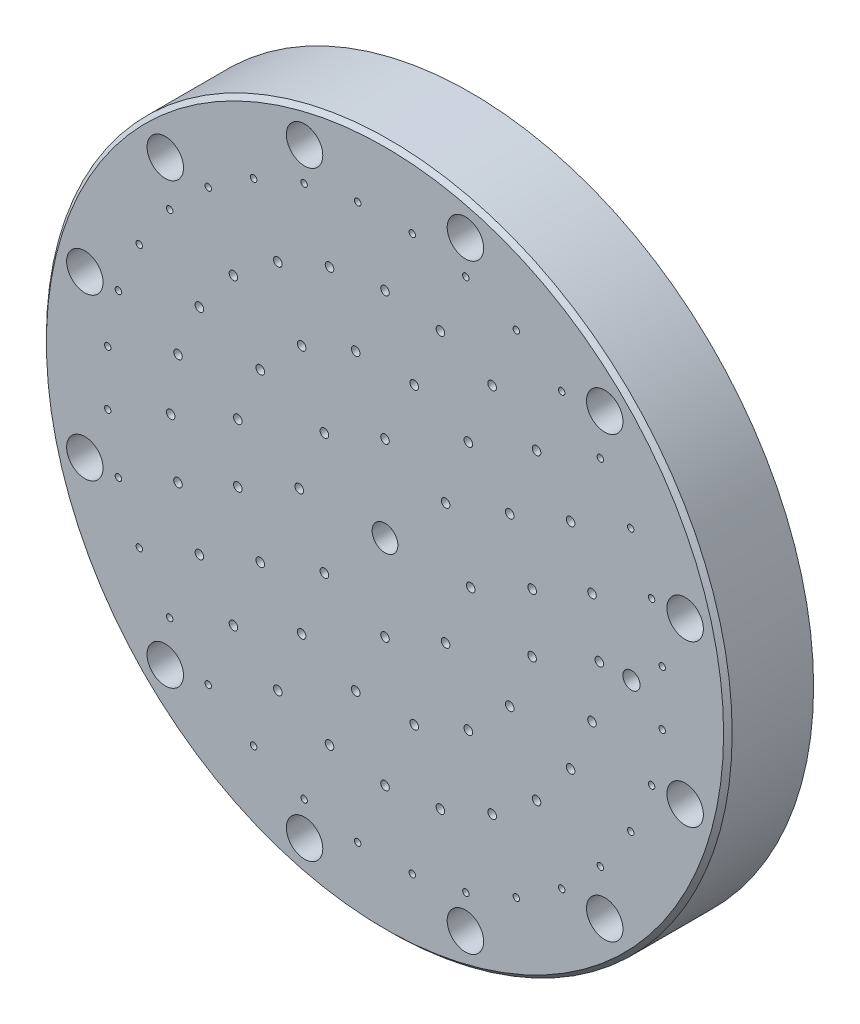
SolidWorks part; units mm, degrees
ref_plane "前视基准面" through (0, 0, 0) normal (0, 0, 1) x (1, 0, 0)
ref_plane "上视基准面" through (0, 0, 0) normal (0, 1, 0) x (1, 0, 0)
ref_plane "右视基准面" through (0, 0, 0) normal (1, 0, 0) x (0, 0, -1)
sketch "草图1" plane through (0, 0, 0) normal (0, 0, 1) x (1, 0, 0)
  circle A0 centre (0, 0) radius 80
extrude "凸台-拉伸1" add sketch "草图1" along normal blind 20
sketch "草图2" plane through (0, 0, 0) normal (0, 0, 1) x (1, 0, 0)
  circle A0 centre (0, 0) radius 23
  circle A1 centre (0, 0) radius 17
extrude "切除-拉伸1" cut sketch "草图2" along normal blind 8
sketch "草图3" plane through (0, 0, 0) normal (0, 0, 1) x (1, 0, 0)
  circle A0 centre (0, 0) radius 38
  circle A1 centre (0, 0) radius 32
extrude "切除-拉伸2" cut sketch "草图3" along normal blind 8
sketch "草图4" plane through (0, 0, 0) normal (0, 0, 1) x (1, 0, 0)
  circle A0 centre (0, 0) radius 53
  circle A1 centre (0, 0) radius 47
extrude "切除-拉伸3" cut sketch "草图4" along normal blind 8
sketch "草图5" plane through (0, 0, 0) normal (0, 0, 1) x (1, 0, 0)
  circle A0 centre (0, 0) radius 68
  circle A1 centre (0, 0) radius 62
extrude "切除-拉伸4" cut sketch "草图5" along normal blind 8
ref_plane "基准面1" through (0, 0, 8) normal (0, 0, 1) x (1, 0, 0)
sketch "草图6" plane through (0, 0, 8) normal (0, 0, 1) x (1, 0, 0)
  circle A0 centre (20, 0) radius 1
  circle A1 centre (14.1421, 14.1421) radius 1
  circle A2 centre (0, 20) radius 1
  circle A3 centre (-14.1421, 14.1421) radius 1
  circle A4 centre (-20, 0) radius 1
  circle A5 centre (-14.1421, -14.1421) radius 1
  circle A6 centre (0, -20) radius 1
  circle A7 centre (14.1421, -14.1421) radius 1
extrude "切除-拉伸5" cut sketch "草图6" along normal blind 12
sketch "草图7" plane through (0, 0, 8) normal (0, 0, 1) x (1, 0, 0)
  circle A0 centre (34.3275, 6.8282) radius 1
  circle A1 centre (29.1014, 19.445) radius 1
  circle A2 centre (19.445, 29.1014) radius 1
  circle A3 centre (6.8282, 34.3275) radius 1
  circle A4 centre (-6.8282, 34.3275) radius 1
  circle A5 centre (-19.445, 29.1014) radius 1
  circle A6 centre (-29.1014, 19.445) radius 1
  circle A7 centre (-34.3275, 6.8282) radius 1
  circle A8 centre (-34.3275, -6.8282) radius 1
  circle A9 centre (-29.1014, -19.445) radius 1
  circle A10 centre (-19.445, -29.1014) radius 1
  circle A11 centre (-6.8282, -34.3275) radius 1
  circle A12 centre (6.8282, -34.3275) radius 1
  circle A13 centre (19.445, -29.1014) radius 1
  circle A14 centre (29.1014, -19.445) radius 1
  circle A15 centre (34.3275, -6.8282) radius 1
extrude "切除-拉伸6" cut sketch "草图7" along normal blind 12
sketch "草图8" plane through (0, 0, 8) normal (0, 0, 1) x (1, 0, 0)
  circle A0 centre (50, 0) radius 1
  circle A1 centre (48.2963, 12.941) radius 1
  circle A2 centre (43.3013, 25) radius 1
  circle A3 centre (35.3553, 35.3553) radius 1
  circle A4 centre (25, 43.3013) radius 1
  circle A5 centre (12.941, 48.2963) radius 1
  circle A6 centre (0, 50) radius 1
  circle A7 centre (-12.941, 48.2963) radius 1
  circle A8 centre (-25, 43.3013) radius 1
  circle A9 centre (-35.3553, 35.3553) radius 1
  circle A10 centre (-43.3013, 25) radius 1
  circle A11 centre (-48.2963, 12.941) radius 1
  circle A12 centre (-50, 0) radius 1
  circle A13 centre (-48.2963, -12.941) radius 1
  circle A14 centre (-43.3013, -25) radius 1
  circle A15 centre (-35.3553, -35.3553) radius 1
  circle A16 centre (-25, -43.3013) radius 1
  circle A17 centre (-12.941, -48.2963) radius 1
  circle A18 centre (0, -50) radius 1
  circle A19 centre (12.941, -48.2963) radius 1
  circle A20 centre (25, -43.3013) radius 1
  circle A21 centre (35.3553, -35.3553) radius 1
  circle A22 centre (43.3013, -25) radius 1
  circle A23 centre (48.2963, -12.941) radius 1
extrude "切除-拉伸7" cut sketch "草图8" along normal blind 12
sketch "草图9" plane through (0, 0, 8) normal (0, 0, 1) x (1, 0, 0)
  circle A0 centre (64.687, 6.3711) radius 0.75
  circle A1 centre (62.2011, 18.8685) radius 0.75
  circle A2 centre (57.3249, 30.6408) radius 0.75
  circle A3 centre (50.2457, 41.2356) radius 0.75
  circle A4 centre (41.2356, 50.2457) radius 0.75
  circle A5 centre (30.6408, 57.3249) radius 0.75
  circle A6 centre (18.8685, 62.2011) radius 0.75
  circle A7 centre (6.3711, 64.687) radius 0.75
  circle A8 centre (-6.3711, 64.687) radius 0.75
  circle A9 centre (-18.8685, 62.2011) radius 0.75
  circle A10 centre (-30.6408, 57.3249) radius 0.75
  circle A11 centre (-41.2356, 50.2457) radius 0.75
  circle A12 centre (-50.2457, 41.2356) radius 0.75
  circle A13 centre (-57.3249, 30.6408) radius 0.75
  circle A14 centre (-62.2011, 18.8685) radius 0.75
  circle A15 centre (-64.687, 6.3711) radius 0.75
  circle A16 centre (-64.687, -6.3711) radius 0.75
  circle A17 centre (-62.2011, -18.8685) radius 0.75
  circle A18 centre (-57.3249, -30.6408) radius 0.75
  circle A19 centre (-50.2457, -41.2356) radius 0.75
  circle A20 centre (-41.2356, -50.2457) radius 0.75
  circle A21 centre (-30.6408, -57.3249) radius 0.75
  circle A22 centre (-18.8685, -62.2011) radius 0.75
  circle A23 centre (-6.3711, -64.687) radius 0.75
  circle A24 centre (6.3711, -64.687) radius 0.75
  circle A25 centre (18.8685, -62.2011) radius 0.75
  circle A26 centre (30.6408, -57.3249) radius 0.75
  circle A27 centre (41.2356, -50.2457) radius 0.75
  circle A28 centre (50.2457, -41.2356) radius 0.75
  circle A29 centre (57.3249, -30.6408) radius 0.75
  circle A30 centre (62.2011, -18.8685) radius 0.75
  circle A31 centre (64.687, -6.3711) radius 0.75
extrude "切除-拉伸8" cut sketch "草图9" along normal blind 12
sketch "草图10" plane through (0, 0, 0) normal (0, 0, 1) x (1, 0, 0)
  circle A0 centre (0, 0) radius 3
extrude "切除-拉伸9" cut sketch "草图10" against normal mid plane 322
ref_plane "基准面2" through (0, 0, 20) normal (0, 0, 1) x (1, 0, 0)
sketch "草图11" plane through (0, 0, 20) normal (0, 0, 1) x (1, 0, 0)
  circle A0 centre (57.5, 0) radius 2
extrude "切除-拉伸10" cut sketch "草图11" against normal blind 6
sketch "草图12" plane through (0, 0, 0) normal (0, 0, 1) x (1, 0, 0)
  circle A0 centre (70.0296, 18.7644) radius 4.25
  circle A1 centre (51.2652, 51.2652) radius 4.25
  circle A2 centre (18.7644, 70.0296) radius 4.25
  circle A3 centre (-18.7644, 70.0296) radius 4.25
  circle A4 centre (-51.2652, 51.2652) radius 4.25
  circle A5 centre (-70.0296, 18.7644) radius 4.25
  circle A6 centre (-70.0296, -18.7644) radius 4.25
  circle A7 centre (-51.2652, -51.2652) radius 4.25
  circle A8 centre (-18.7644, -70.0296) radius 4.25
  circle A9 centre (18.7644, -70.0296) radius 4.25
  circle A10 centre (51.2652, -51.2652) radius 4.25
  circle A11 centre (70.0296, -18.7644) radius 4.25
extrude "切除-拉伸11" cut sketch "草图12" against normal mid plane 322
chamfer "倒角1" distance 1 angle 45 1 edges at (80, 0, 20)
